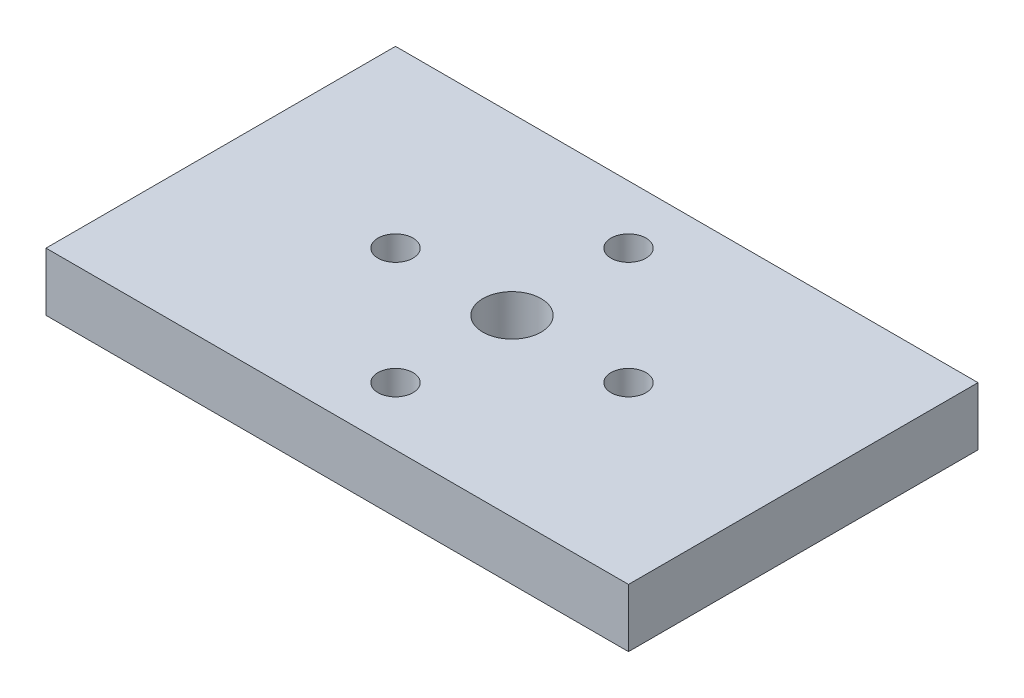
SolidWorks part; units mm, degrees
ref_plane "前视基准面" through (0, 0, 0) normal (0, 0, 1) x (1, 0, 0)
ref_plane "上视基准面" through (0, 0, 0) normal (0, 1, 0) x (1, 0, 0)
ref_plane "右视基准面" through (0, 0, 0) normal (1, 0, 0) x (0, 0, -1)
other "Configuration Table"
sketch "草图1" plane through (0, 0, 0) normal (0, 1, 0) x (1, 0, 0)
  line L1 (-50, -30) -> (50, -30)
  line L2 (-50, -30) -> (-50, 30)
  line L3 (-50, 30) -> (50, 30)
  line L4 (50, -30) -> (50, 30)
  line L5 (-50, -30) -> (50, 30) construction
  line L6 (-50, 30) -> (50, -30) construction
  point P0 (0, 0)
extrude "凸台-拉伸1" add sketch "草图1" along normal blind 10
sketch "草图2" plane through (0, 0, 0) normal (0, 1, 0) x (1, 0, 0)
  circle A0 centre (0, 0) radius 5
extrude "切除-拉伸1" cut sketch "草图2" along normal blind 20
sketch "草图3" plane through (0, 0, 0) normal (0, 1, 0) x (1, 0, 0)
  circle A0 centre (20, 0) radius 3
extrude "切除-拉伸2" cut sketch "草图3" along normal blind 20
pattern_circular "阵列(圆周)1" count 4 over 360 about axis through (0, 0, 0) along (0, 1, 0) of "切除-拉伸2"
